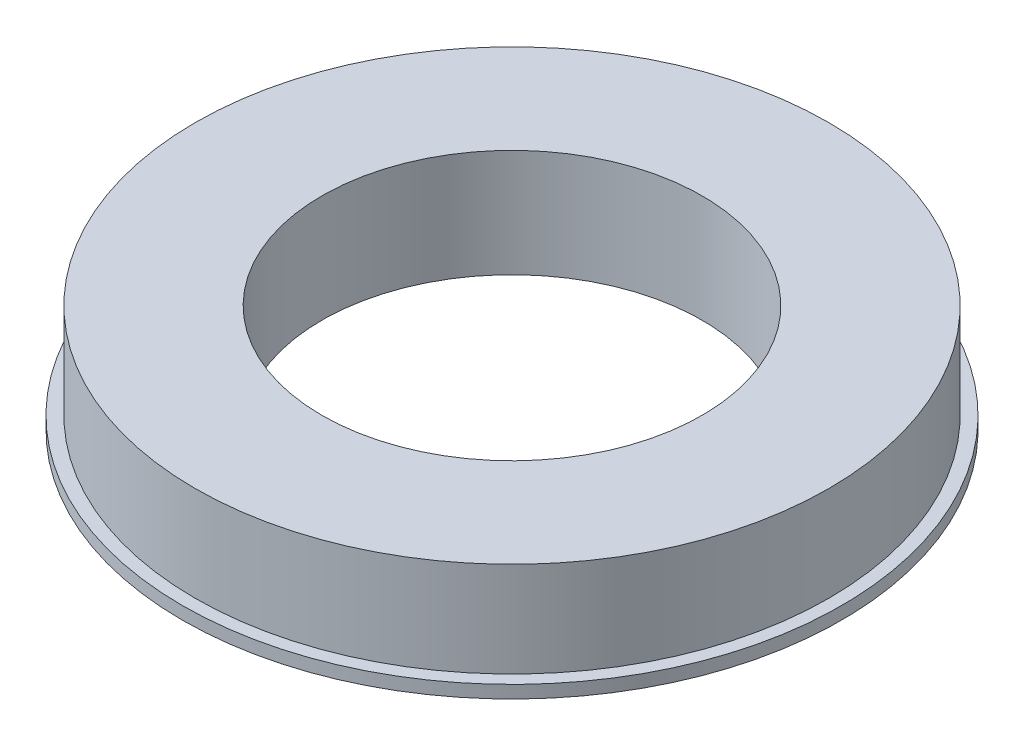
SolidWorks part; units mm, degrees
ref_plane "Front Plane" through (0, 0, 0) normal (0, 0, 1) x (1, 0, 0)
ref_plane "Top Plane" through (0, 0, 0) normal (0, 1, 0) x (1, 0, 0)
ref_plane "Right Plane" through (0, 0, 0) normal (1, 0, 0) x (0, 0, -1)
sketch "Sketch1" plane through (0, 0, 0) normal (0, 1, 0) x (1, 0, 0)
  circle A0 centre (0, 0) radius 66.04
  dimension "D1" = 132.08
extrude "Boss-Extrude1" add sketch "Sketch1" along normal blind 2.54 contours A0
sketch "Sketch2" plane through (0, 2.54, 0) normal (0, 1, 0) x (1, 0, 0)
  circle A0 centre (0, 0) radius 63.5
  dimension "D1" = 127
extrude "Boss-Extrude2" add sketch "Sketch2" along normal blind 19.05
sketch "Sketch3" plane through (0, 21.59, 0) normal (0, 1, 0) x (1, 0, 0)
  circle A0 centre (0, 0) radius 38.1
  dimension "D1" = 76.2
extrude "Cut-Extrude1" cut sketch "Sketch3" against normal through all contours A0
